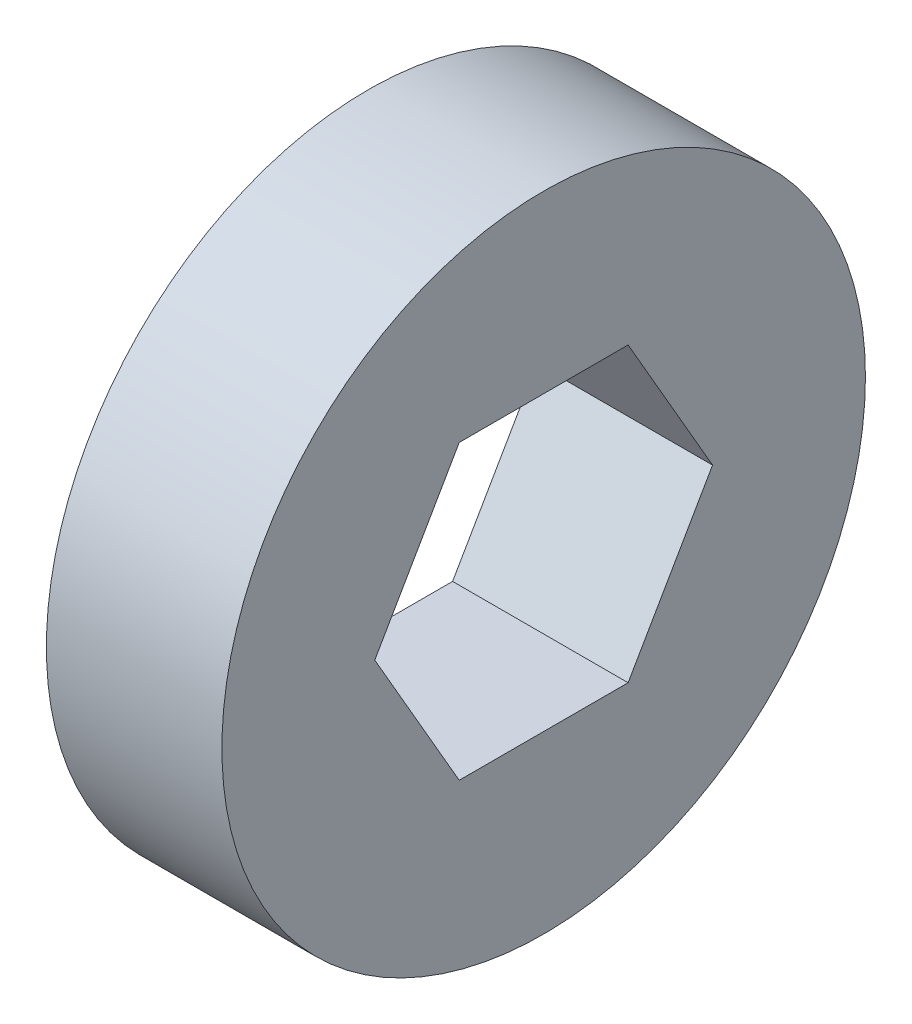
SolidWorks part; units mm, degrees
material "ABS"
ref_plane "前视基准面" through (0, 0, 0) normal (0, 0, 1) x (1, 0, 0)
ref_plane "上视基准面" through (0, 0, 0) normal (0, 1, 0) x (1, 0, 0)
ref_plane "右视基准面" through (0, 0, 0) normal (1, 0, 0) x (0, 0, -1)
other "Configuration Table"
sketch "草图1" plane through (0, 0, 0) normal (1, 0, 0) x (0, 0, -1)
  line L1 (2.8868, 0) -> (1.4434, 2.5)
  line L2 (1.4434, 2.5) -> (-1.4434, 2.5)
  line L3 (-1.4434, 2.5) -> (-2.8868, 0)
  line L4 (-2.8868, 0) -> (-1.4434, -2.5)
  line L5 (-1.4434, -2.5) -> (1.4434, -2.5)
  line L6 (1.4434, -2.5) -> (2.8868, 0)
  circle A0 centre (0, 0) radius 2.5 construction
  circle A1 centre (0, 0) radius 5.5
  dimension "D1" = 5
  dimension "D2" = 11
extrude "凸台-拉伸1" add sketch "草图1" along normal blind 3
